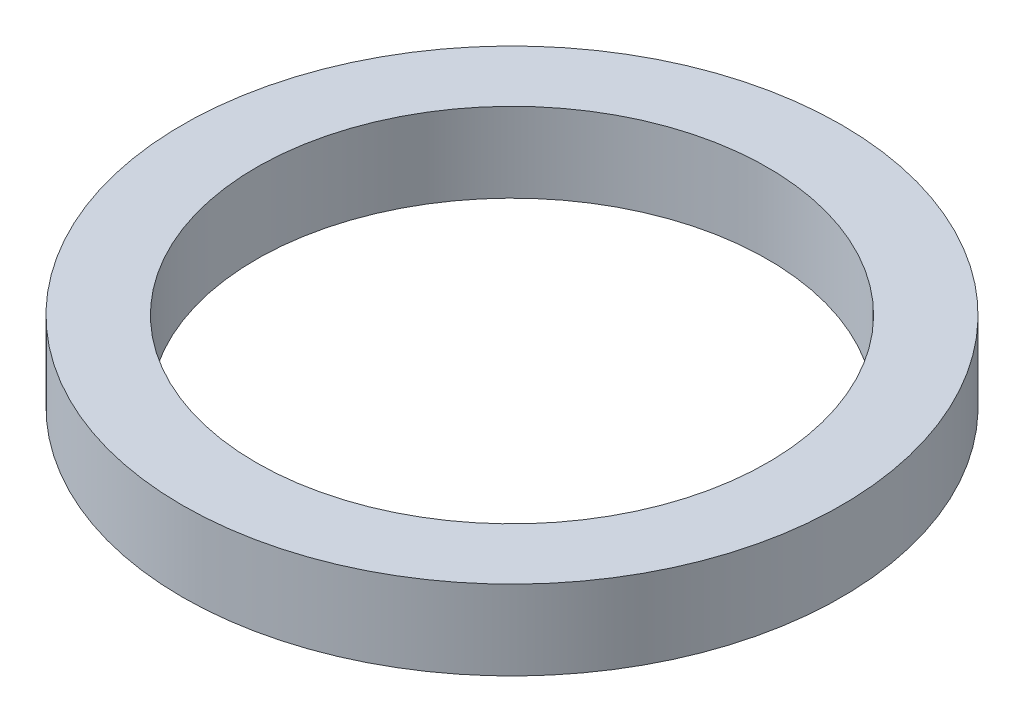
SolidWorks part; units mm, degrees
ref_plane "Front Plane" through (0, 0, 0) normal (0, 0, 1) x (1, 0, 0)
ref_plane "Top Plane" through (0, 0, 0) normal (0, 1, 0) x (1, 0, 0)
ref_plane "Right Plane" through (0, 0, 0) normal (1, 0, 0) x (0, 0, -1)
sketch "Sketch1" plane through (0, 0, 0) normal (0, 1, 0) x (1, 0, 0)
  circle A0 centre (0, 0) radius 22.5
  circle A1 centre (0, 0) radius 29
  dimension "D1" = 45
  dimension "D2" = 58
extrude "Boss-Extrude1" add sketch "Sketch1" along normal mid plane 7
